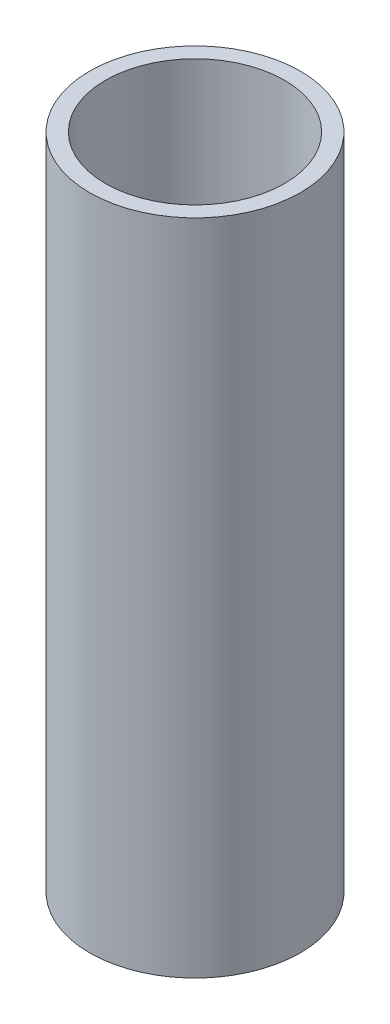
SolidWorks part; units mm, degrees
ref_plane "前视基准面" through (0, 0, 0) normal (0, 0, 1) x (1, 0, 0)
ref_plane "上视基准面" through (0, 0, 0) normal (0, 1, 0) x (1, 0, 0)
ref_plane "右视基准面" through (0, 0, 0) normal (1, 0, 0) x (0, 0, -1)
other "Configuration Table"
sketch "草图1" plane through (0, 0, 0) normal (0, 1, 0) x (1, 0, 0)
  circle A14 centre (0, 0) radius 16
  circle A15 centre (0, 0) radius 13.6
  dimension "D1" = 32
  dimension "D2" = 2.4
extrude "凸台-拉伸1" add sketch "草图1" along normal blind 100
